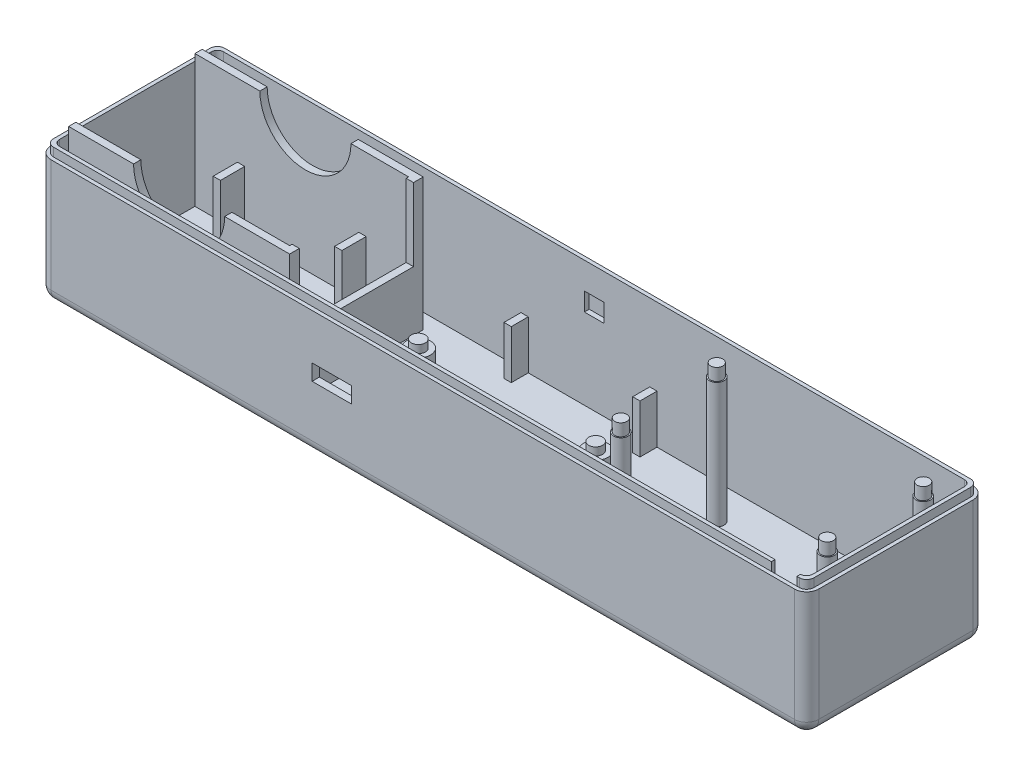
SolidWorks part; units mm, degrees
ref_plane "Front Plane" through (0, 0, 0) normal (0, 0, 1) x (1, 0, 0)
ref_plane "Top Plane" through (0, 0, 0) normal (0, 1, 0) x (1, 0, 0)
ref_plane "Right Plane" through (0, 0, 0) normal (1, 0, 0) x (0, 0, -1)
sketch "Sketch1" plane through (0, 0, 0) normal (0, 1, 0) x (1, 0, 0)
  line L1 (-80.2894, -18.669) -> (80.2894, -18.669)
  line L2 (-80.2894, -18.669) -> (-80.2894, 18.669)
  line L3 (-80.2894, 18.669) -> (80.2894, 18.669)
  line L4 (80.2894, -18.669) -> (80.2894, 18.669)
  line L5 (-80.2894, -18.669) -> (80.2894, 18.669) construction
  line L6 (-80.2894, 18.669) -> (80.2894, -18.669) construction
  point P0 (0, 0)
  dimension "D1" = 160.5788
  dimension "D2" = 37.338
extrude "Boss-Extrude1" add sketch "Sketch1" along normal blind 27.94
sketch "Sketch2" plane through (0, 27.94, 0) normal (0, 1, 0) x (1, 0, 0)
  line L0 (-80.2894, 18.669) -> (-80.2894, -18.669) construction
  line L1 (-78.7654, 17.145) -> (78.7654, 17.145)
  line L2 (-78.7654, 17.145) -> (-78.7654, -17.145)
  line L3 (-78.7654, -17.145) -> (78.7654, -17.145)
  line L4 (78.7654, 17.145) -> (78.7654, -17.145)
  line L5 (-78.7654, 17.145) -> (78.7654, -17.145) construction
  line L6 (-78.7654, -17.145) -> (78.7654, 17.145) construction
  line L7 (-80.2894, -18.669) -> (80.2894, -18.669) construction
  point P0 (0, 0)
  dimension "D1" = 1.524
  dimension "D2" = 1.524
extrude "Cut-Extrude3" cut sketch "Sketch2" against normal offset from surface (26.289 mm away) 1.651 up to face at (0, 0, 0)
fillet "Fillet1" radius 2.54 8 edges at (80.2894, 0, 0) (80.2894, 13.97, -18.669) (0, 0, -18.669) (0, 0, 18.669) (-80.2894, 0, 0) (-80.2894, 13.97, -18.669) (-80.2894, 13.97, 18.669) (80.2894, 13.97, 18.669)
fillet "Fillet2" radius 1.27 4 edges at (78.7654, 14.7955, 17.145) (78.7654, 14.7955, -17.145) (-78.7654, 14.7955, 17.145) (-78.7654, 14.7955, -17.145)
sketch "Sketch3" plane through (0, 1.651, 0) normal (0, 1, 0) x (1, 0, 0)
  line L0 (-78.7654, 15.875) -> (-78.7654, -15.875) construction
  line L1 (-78.7654, 13.97) -> (-32.5374, 13.97)
  line L2 (-78.7654, 13.97) -> (-78.7654, -13.97)
  line L3 (-78.7654, -13.97) -> (-32.5374, -13.97)
  line L4 (-32.5374, 13.97) -> (-32.5374, -13.97)
  line L5 (0, 0) -> (-41.9588, 0) construction
  dimension "D1" = 27.94
  dimension "D2" = 46.228
extrude "Boss-Extrude2" add sketch "Sketch3" along normal blind 27.686 contours L2 L1 L4 L3
sketch "Sketch8" plane through (0, 29.337, 0) normal (0, 1, 0) x (1, 0, 0)
  line L0 (-32.5374, 0) -> (-78.7654, 0) construction
  line L1 (-34.0614, 12.446) -> (-78.7654, 12.446)
  line L2 (-34.0614, 12.446) -> (-34.0614, -12.446)
  line L3 (-34.0614, -12.446) -> (-78.7654, -12.446)
  line L4 (-78.7654, 12.446) -> (-78.7654, -12.446)
  line L5 (-32.5374, 13.97) -> (-32.5374, -13.97) construction
  line L6 (-78.7654, 13.97) -> (-78.7654, -13.97) construction
  line L7 (-78.7654, 13.97) -> (-32.5374, 13.97) construction
  dimension "D1" = 1.524
  dimension "D2" = 1.524
extrude "Cut-Extrude6" cut sketch "Sketch8" against normal up to surface (27.686 mm away) up to face at (-18.5505, 1.651, 0)
sketch "Sketch7" plane through (0, 0, 13.97) normal (0, 0, 1) x (1, 0, 0)
  line L0 (-78.7654, 29.337) -> (-32.5374, 29.337) construction
  circle A0 centre (-55.6514, 29.337) radius 9.525
  dimension "D1" = 19.05
extrude "Cut-Extrude5" cut sketch "Sketch7" against normal up to surface (27.94 mm away) up to face at (-60.2742, 17.9832, -13.97)
sketch "Sketch9" plane through (-34.0614, 0, 0) normal (-1, 0, 0) x (0, 0, 1)
  line L0 (12.446, 29.337) -> (-12.446, 29.337) construction
  line L1 (-11.938, 29.337) -> (11.938, 29.337)
  line L2 (-11.938, 29.337) -> (-11.938, 14.097)
  line L3 (-11.938, 14.097) -> (11.938, 14.097)
  line L4 (11.938, 29.337) -> (11.938, 14.097)
  line L5 (-12.446, 1.651) -> (-12.446, 29.337) construction
  line L6 (12.446, 1.651) -> (12.446, 29.337) construction
  dimension "D1" = 0.508
  dimension "D2" = 0.508
  dimension "D3" = 15.24
extrude "Cut-Extrude7" cut sketch "Sketch9" against normal up to next
sketch "Sketch10" plane through (0, 1.651, 0) normal (0, 1, 0) x (1, 0, 0)
  line L0 (0, 0) -> (57.9787, 0) construction
  line L1 (-34.0614, 11.938) -> (-34.0614, -11.938) construction
  line L2 (-23.9014, 16.51) -> (21.8186, 16.51) construction
  line L3 (-23.9014, 16.51) -> (-23.9014, -16.51) construction
  line L4 (-23.9014, -16.51) -> (21.8186, -16.51) construction
  line L5 (21.8186, 16.51) -> (21.8186, -16.51) construction
  line L6 (77.4954, 17.145) -> (-77.4954, 17.145) construction
  line L7 (-15.2654, 17.145) -> (-13.7414, 17.145)
  line L8 (-15.2654, 17.145) -> (-15.2654, 13.589)
  line L9 (-15.2654, 13.589) -> (-13.7414, 13.589)
  line L10 (-13.7414, 17.145) -> (-13.7414, 13.589)
  line L11 (11.6586, 17.145) -> (13.1826, 17.145)
  line L12 (11.6586, 17.145) -> (11.6586, 13.589)
  line L13 (11.6586, 13.589) -> (13.1826, 13.589)
  line L14 (13.1826, 17.145) -> (13.1826, 13.589)
  line L15 (-15.2654, -13.589) -> (-13.7414, -13.589)
  line L16 (-15.2654, -13.589) -> (-15.2654, -17.145)
  line L17 (-15.2654, -17.145) -> (-13.7414, -17.145)
  line L18 (-13.7414, -13.589) -> (-13.7414, -17.145)
  line L19 (11.6586, -13.589) -> (13.1826, -13.589)
  line L20 (11.6586, -13.589) -> (11.6586, -17.145)
  line L21 (11.6586, -17.145) -> (13.1826, -17.145)
  line L22 (13.1826, -13.589) -> (13.1826, -17.145)
  line L23 (-77.4954, -17.145) -> (77.4954, -17.145) construction
  line L24 (-19.5834, 0) -> (17.5006, 0) construction
  line L25 (-1.0414, 0) -> (-1.0414, 27.8504) construction
  circle A0 centre (-19.5834, 0) radius 2.54
  circle A1 centre (17.5006, 0) radius 2.54
  dimension "D1" = 37.084
  dimension "D2" = 5.08
  dimension "D3" = 33.02
  dimension "D5" = 4.318
  dimension "D6" = 4.318
  dimension "D4" = 45.72
  dimension "D7" = 10.16
  dimension "D8" = 3.556
  dimension "D9" = 1.524
  dimension "D10" = 25.4
  dimension "D11" = 25.4
extrude "Boss-Extrude5" add sketch "Sketch10" along normal blind 10.16
sketch "Sketch11" plane through (0, 11.811, 0) normal (0, 1, 0) x (1, 0, 0)
  circle A0 centre (17.5006, 0) radius 1.4605
  circle A1 centre (-19.5834, 0) radius 1.4605
  dimension "D1" = 2.921
extrude "Boss-Extrude6" add sketch "Sketch11" along normal blind 1.651
sketch "Sketch12" plane through (0, 0, 18.669) normal (0, 0, 1) x (1, 0, 0)
  line L0 (77.7494, 0) -> (-77.7494, 0) construction
  line L1 (-23.1394, 16.6683) -> (-14.921, 16.6683)
  line L2 (-23.1394, 16.6683) -> (-23.1394, 13.335)
  line L3 (-23.1394, 13.335) -> (-14.921, 13.335)
  line L4 (-14.921, 16.6683) -> (-14.921, 13.335)
  line L5 (-80.2894, 27.94) -> (-80.2894, 2.54) construction
  dimension "D1" = 13.335
  dimension "D2" = 3.3333
  dimension "D3" = 8.2184
  dimension "D4" = 57.15
extrude "Cut-Extrude8" cut sketch "Sketch12" against normal up to next
sketch "Sketch13" plane through (0, 1.651, 0) normal (0, 1, 0) x (1, 0, 0)
  line L0 (78.7654, 0) -> (0, 0) construction
  line L1 (32.7914, 10.033) -> (75.9714, 10.033) construction
  line L2 (32.7914, 10.033) -> (32.7914, -10.033) construction
  line L3 (32.7914, -10.033) -> (75.9714, -10.033) construction
  line L4 (75.9714, 10.033) -> (75.9714, -10.033) construction
  line L5 (78.7654, -15.875) -> (78.7654, 15.875) construction
  circle A0 centre (32.7914, 10.033) radius 1.524
  circle A1 centre (75.9714, 10.033) radius 1.524
  circle A2 centre (75.9714, -10.033) radius 1.524
  circle A3 centre (32.7914, -10.033) radius 1.524
  dimension "D1" = 3.048
  dimension "D2" = 2.794
  dimension "D3" = 43.18
  dimension "D4" = 20.066
extrude "Boss-Extrude7" add sketch "Sketch13" along normal blind 26.162
sketch "Sketch14" plane through (0, 27.813, 0) normal (0, 1, 0) x (1, 0, 0)
  circle A0 centre (32.7914, 10.033) radius 1.27
  circle A1 centre (32.7914, -10.033) radius 1.27
  circle A2 centre (75.9714, -10.033) radius 1.27
  circle A3 centre (75.9714, 10.033) radius 1.27
  dimension "D1" = 2.54
extrude "Boss-Extrude8" add sketch "Sketch14" along normal blind 2.54
sketch "Sketch15" plane through (0, 1.651, 0) normal (0, 1, 0) x (1, 0, 0)
  line L0 (-78.7654, -12.446) -> (-34.0614, -12.446) construction
  line L1 (-42.9514, 12.446) -> (-44.4754, 12.446)
  line L2 (-42.9514, 12.446) -> (-42.9514, 7.366)
  line L3 (-42.9514, 7.366) -> (-44.4754, 7.366)
  line L4 (-44.4754, 12.446) -> (-44.4754, 7.366)
  line L5 (-42.9514, -7.366) -> (-44.4754, -7.366)
  line L6 (-42.9514, -7.366) -> (-42.9514, -12.446)
  line L7 (-42.9514, -12.446) -> (-44.4754, -12.446)
  line L8 (-44.4754, -7.366) -> (-44.4754, -12.446)
  line L9 (-68.3514, 12.446) -> (-69.8754, 12.446)
  line L10 (-68.3514, 12.446) -> (-68.3514, 7.366)
  line L11 (-68.3514, 7.366) -> (-69.8754, 7.366)
  line L12 (-69.8754, 12.446) -> (-69.8754, 7.366)
  line L13 (-69.8754, -12.446) -> (-68.3514, -12.446)
  line L14 (-69.8754, -12.446) -> (-69.8754, -7.366)
  line L15 (-69.8754, -7.366) -> (-68.3514, -7.366)
  line L16 (-68.3514, -12.446) -> (-68.3514, -7.366)
  line L17 (-34.0614, 12.446) -> (-78.7654, 12.446) construction
  line L18 (-34.0614, -12.446) -> (-34.0614, 12.446) construction
  line L19 (-78.7654, 12.446) -> (-78.7654, -12.446) construction
  point P22 (-42.9514, 9.906)
  dimension "D1" = 1.524
  dimension "D2" = 8.89
  dimension "D3" = 8.89
  dimension "D4" = 5.08
extrude "Boss-Extrude9" add sketch "Sketch15" along normal blind 12.446
sketch "Sketch16" plane through (0, 27.94, 0) normal (0, 1, 0) x (1, 0, 0)
  line L0 (77.7494, 18.669) -> (-77.7494, 18.669) construction
  line L1 (-79.5274, 17.907) -> (79.5274, 17.907)
  line L2 (-79.5274, 17.907) -> (-79.5274, -17.907)
  line L3 (-79.5274, -17.907) -> (79.5274, -17.907)
  line L4 (79.5274, 17.907) -> (79.5274, -17.907)
  line L5 (-80.2894, 16.129) -> (-80.2894, -16.129) construction
  line L6 (-77.7494, -18.669) -> (77.7494, -18.669) construction
  line L7 (80.2894, -16.129) -> (80.2894, 16.129) construction
  dimension "D1" = 0.762
  dimension "D2" = 0.762
  dimension "D3" = 0.762
  dimension "D4" = 0.762
extrude "Cut-Extrude9" cut sketch "Sketch16" against normal blind 1.778 flip side to cut
fillet "Fillet3" radius 1.524 4 edges at (-79.5274, 27.051, 17.907) (79.5274, 27.051, 17.907) (79.5274, 27.051, -17.907) (-79.5274, 27.051, -17.907)
sketch "Sketch17" plane through (0, 27.94, 0) normal (0, 1, 0) x (1, 0, 0)
  line L0 (-78.0034, -17.907) -> (78.0034, -17.907) construction
  line L1 (77.4954, -17.145) -> (72.1614, -17.145)
  line L2 (77.4954, -17.145) -> (77.4954, -17.907)
  line L3 (77.4954, -17.907) -> (72.1614, -17.907)
  line L4 (72.1614, -17.145) -> (72.1614, -17.907)
  dimension "D1" = 5.334
extrude "Cut-Extrude10" cut sketch "Sketch17" against normal blind 8.89
sketch "Sketch18" plane through (0, 0, 17.145) normal (0, 0, -1) x (-1, 0, 0)
  line L0 (-78.7654, 1.651) -> (-78.7654, 27.94) construction
  line L1 (-2.0574, 22.352) -> (2.0066, 22.352)
  line L2 (-2.0574, 22.352) -> (-2.0574, 18.542)
  line L3 (-2.0574, 18.542) -> (2.0066, 18.542)
  line L4 (2.0066, 22.352) -> (2.0066, 18.542)
  line L5 (77.4954, 27.94) -> (-72.1614, 27.94) construction
  dimension "D1" = 4.064
  dimension "D2" = 76.708
  dimension "D3" = 5.588
  dimension "D4" = 3.81
extrude "Cut-Extrude11" cut sketch "Sketch18" against normal blind 1.016
mirror "Mirror1" about plane through (0, 0, 0) normal (0, 0, 1) of "Cut-Extrude11"
sketch "Sketch19" plane through (0, 0, -18.669) normal (0, 0, -1) x (-1, 0, 0)
  line L0 (0, 0) -> (0, 34.4733) construction
  text T0 "THIS SIDE \r\nTO MAGNET"
extrude "Magnet Text" cut sketch "Sketch19" against normal blind 0.1778
